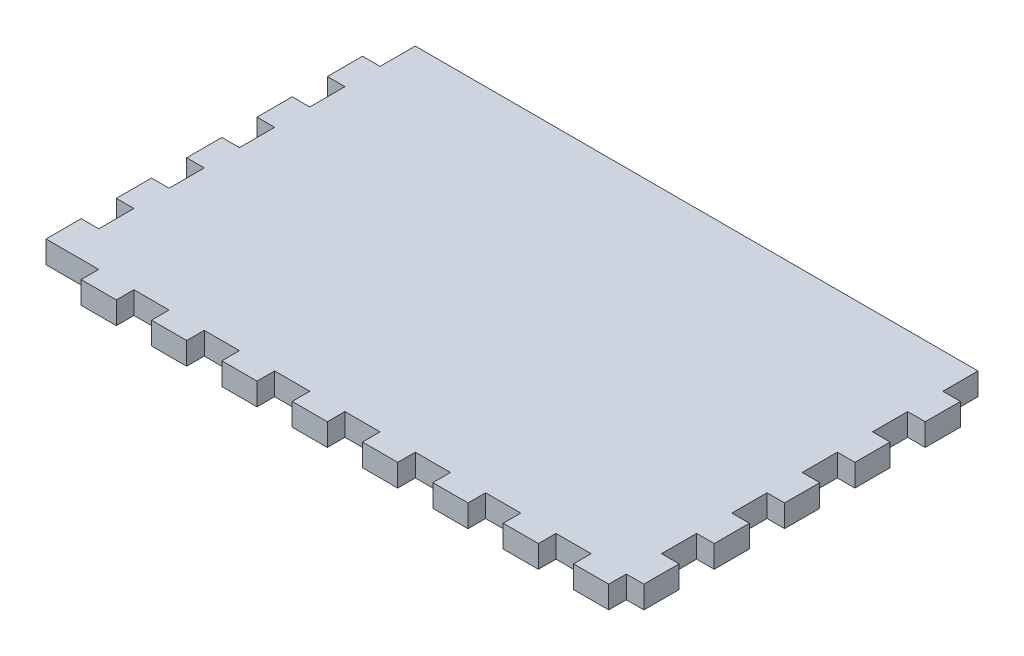
SolidWorks part; units mm, degrees
ref_plane "Front Plane" through (0, 0, 0) normal (0, 0, 1) x (1, 0, 0)
ref_plane "Top Plane" through (0, 0, 0) normal (0, 1, 0) x (1, 0, 0)
ref_plane "Right Plane" through (0, 0, 0) normal (1, 0, 0) x (0, 0, -1)
sketch "Sketch1" plane through (0, 0, 0) normal (0, 1, 0) x (1, 0, 0)
  line L1 (0, 0) -> (80, 0)
  line L2 (0, 0) -> (0, 50)
  line L3 (0, 50) -> (80, 50)
  line L4 (80, 0) -> (80, 50)
  dimension "D1" = 80
  dimension "D2" = 50
extrude "Boss-Extrude1" add sketch "Sketch1" along normal blind 3.175
sketch "Sketch2" plane through (0, 0, 0) normal (-1, 0, 0) x (0, 0, 1)
  line L0 (-50, 0) -> (0, 0) construction
  line L1 (0, 3.175) -> (-5, 3.175)
  line L2 (0, 3.175) -> (0, 0)
  line L3 (0, 0) -> (-5, 0)
  line L4 (-5, 3.175) -> (-5, 0)
  dimension "D1" = 5
extrude "Boss-Extrude2" add sketch "Sketch2" along normal blind 2.5
pattern_linear "LPattern1" count 5 spacing 10 along (0, 0, -1) of "Boss-Extrude2"
sketch "Sketch3" plane through (80, 0, 0) normal (1, 0, 0) x (0, 0, -1)
  line L0 (0, 0) -> (50, 0) construction
  line L1 (0, 3.175) -> (5, 3.175)
  line L2 (0, 3.175) -> (0, 0)
  line L3 (0, 0) -> (5, 0)
  line L4 (5, 3.175) -> (5, 0)
  dimension "D1" = 5
extrude "Boss-Extrude3" add sketch "Sketch3" along normal blind 2.5
pattern_linear "LPattern2" count 5 spacing 10 along (0, 0, -1) of "Boss-Extrude3"
sketch "Sketch4" plane through (0, 0, 0) normal (0, 0, 1) x (1, 0, 0)
  line L0 (-2.5, 0) -> (82.5, 0) construction
  line L1 (80, 0) -> (75, 0)
  line L2 (80, 0) -> (80, 3.175)
  line L3 (80, 3.175) -> (75, 3.175)
  line L4 (75, 0) -> (75, 3.175)
  line L5 (-2.5, 3.175) -> (82.5, 3.175) construction
  line L6 (82.5, 3.175) -> (82.5, 0) construction
  dimension "D1" = 2.5
  dimension "D2" = 5
extrude "Boss-Extrude4" add sketch "Sketch4" along normal blind 2.5
pattern_linear "LPattern3" count 8 spacing 10 along (-1, 0, 0) of "Boss-Extrude4"
